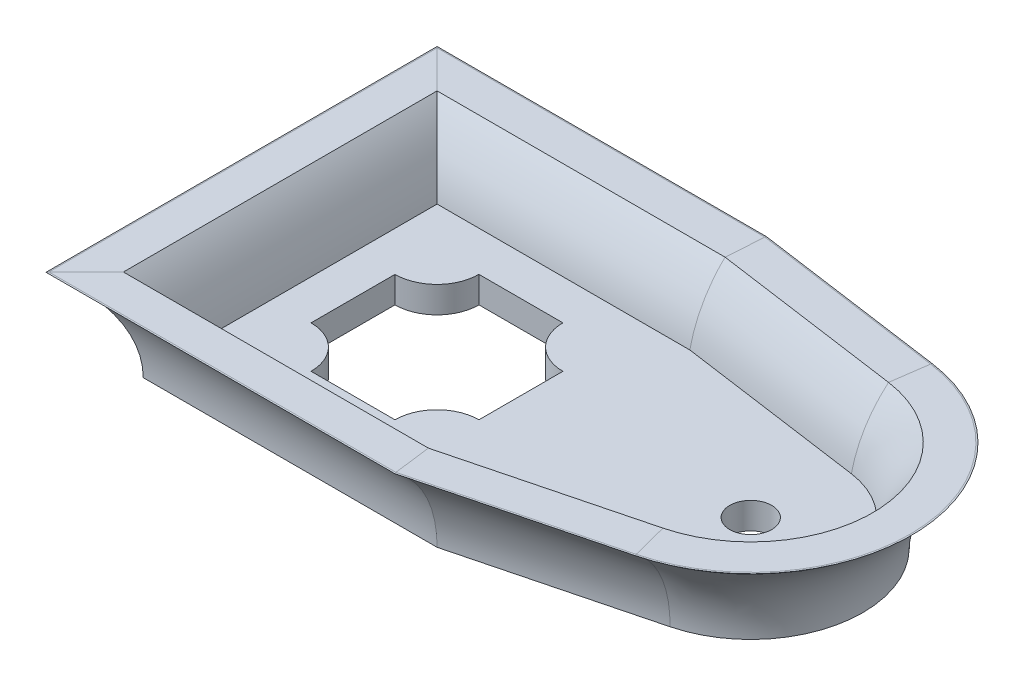
SolidWorks part; units mm, degrees
ref_plane "Front Plane" through (0, 0, 0) normal (0, 0, 1) x (1, 0, 0)
ref_plane "Top Plane" through (0, 0, 0) normal (0, 1, 0) x (1, 0, 0)
ref_plane "Right Plane" through (0, 0, 0) normal (1, 0, 0) x (0, 0, -1)
sketch "Sketch1" plane through (0, 0, 0) normal (1, 0, 0) x (0, 0, -1)
  line L0 (2.62, 0) -> (3.74, 0)
  line L1 (3.74, 0) -> (3.74, 0.63)
  line L2 (3.74, 0.63) -> (3.168, 0.63)
  line L3 (2.3834, 2.18) -> (1.4962, 2.18)
  arc A0 (3.168, 0.63) -> (2.3834, 2.18) centre (0, 0) ccw
  arc A1 (2.62, 0) -> (1.4616, 2.1744) centre (0, 0) ccw
  arc A2 (1.4962, 2.18) -> (1.4616, 2.1744) centre (1.4962, 2.07) ccw
  dimension "D1" = 6.46
  dimension "D2" = 5.24
  dimension "D6" = 0.11
  dimension "D3" = 1.12
  dimension "D4" = 0.63
  dimension "D5" = 2.18
sketch "Sketch2" plane through (0, 0, 0) normal (0, 1, 0) x (1, 0, 0)
  line L0 (0, 2.62) -> (7, 2.62)
  line L1 (7, 2.62) -> (11.4153, 3.7559)
  line L2 (11.1214, 8.9858) -> (6.6067, 9.62)
  line L3 (6.6067, 9.62) -> (0, 9.62)
  line L5 (0, 2.62) -> (0, 9.62)
  arc A0 (11.4153, 3.7559) -> (11.1214, 8.9858) centre (10.75, 6.3417) ccw
  dimension "D3" = 2.67
  dimension "D1" = 7
  dimension "D2" = 7
  dimension "D4" = 10.75
sweep "Sweep1" add profiles "Sketch1" path "Sketch2"
sketch "Sketch3" plane through (1.12, 0, 0) normal (1, 0, 0) x (0, 0, -1)
  line L1 (3.74, 0.63) -> (8.5, 0.63)
  line L2 (3.74, 0.63) -> (3.74, 0)
  line L3 (3.74, 0) -> (8.5, 0)
  line L4 (8.5, 0.63) -> (8.5, 0)
extrude "Boss-Extrude1" add sketch "Sketch3" along normal up to next
sketch "Sketch4" plane through (0, 0.63, 0) normal (0, 1, 0) x (1, 0, 0)
  line L0 (1.4971, 7.12) -> (1.4971, 5.12)
  line L3 (10.25, 6.3417) -> (10.75, 6.3417) construction
  line L6 (4.4971, 8.12) -> (2.4971, 8.12)
  line L7 (5.4971, 5.12) -> (5.4971, 7.12)
  line L8 (2.4971, 4.12) -> (4.4971, 4.12)
  circle A0 centre (10.75, 6.3417) radius 0.5
  arc A1 (1.4971, 5.12) -> (2.4971, 4.12) centre (1.4971, 4.12) cw
  arc A2 (1.4971, 7.12) -> (2.4971, 8.12) centre (1.4971, 8.12) ccw
  arc A4 (4.4971, 8.12) -> (5.4971, 7.12) centre (5.4971, 8.12) ccw
  arc A5 (2.4971, 8.12) -> (1.4971, 7.12) centre (1.4971, 8.12) cw
  arc A6 (5.4971, 5.12) -> (4.4971, 4.12) centre (5.4971, 4.12) ccw
  arc A7 (5.4971, 7.12) -> (4.4971, 8.12) centre (5.4971, 8.12) cw
  arc A8 (2.4971, 4.12) -> (1.4971, 5.12) centre (1.4971, 4.12) ccw
  arc A9 (4.4971, 4.12) -> (5.4971, 5.12) centre (5.4971, 4.12) cw
  point P6 (1.4971, 6.12)
  point P13 (1.4971, 7.2027)
  point P42 (3.4971, 6.12)
  dimension "D1" = 1
  dimension "D4" = 2
  dimension "D3" = 1
  dimension "D2" = 4
  dimension "D5" = 4
extrude "Cut-Extrude1" cut sketch "Sketch4" against normal through all both and the other way through all
